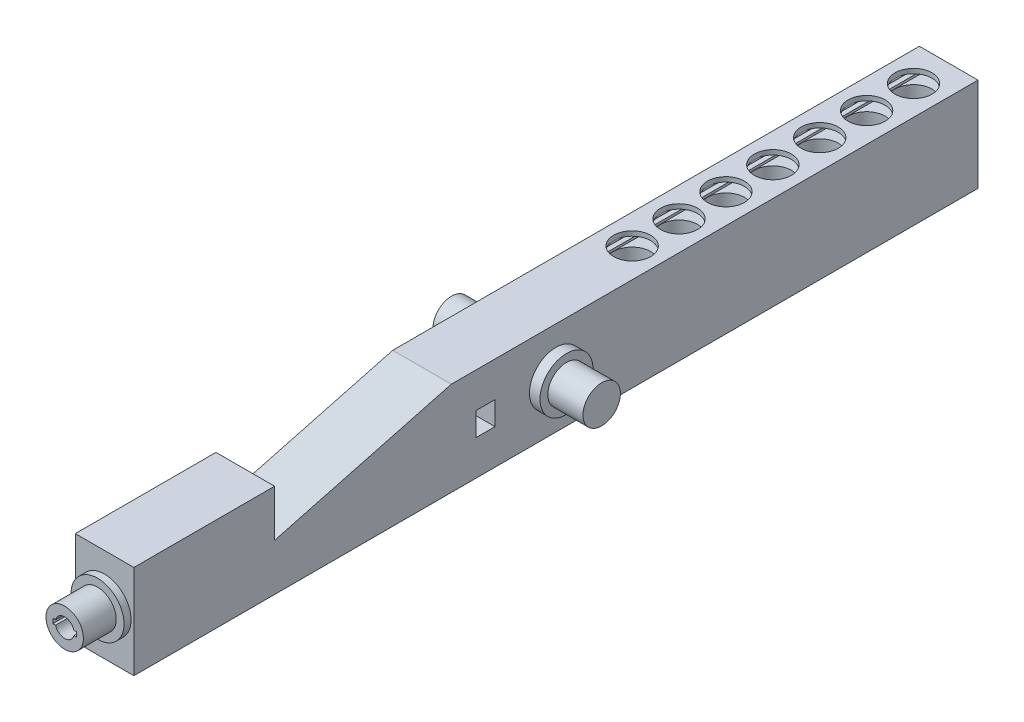
SolidWorks part; units mm, degrees
material "6061 Alloy"
ref_plane "Front Plane" through (0, 0, 0) normal (0, 0, 1) x (1, 0, 0)
ref_plane "Top Plane" through (0, 0, 0) normal (0, 1, 0) x (1, 0, 0)
ref_plane "Right Plane" through (0, 0, 0) normal (1, 0, 0) x (0, 0, -1)
sketch "Sketch1" plane through (0, 0, 0) normal (0, 1, 0) x (1, 0, 0)
  line L1 (-6.25, 90) -> (6.25, 90)
  line L2 (-6.25, 90) -> (-6.25, -90)
  line L3 (-6.25, -90) -> (6.25, -90)
  line L4 (6.25, 90) -> (6.25, -90)
  line L5 (-6.25, 90) -> (6.25, -90) construction
  line L6 (-6.25, -90) -> (6.25, 90) construction
  point P0 (0, 0)
  dimension "D1" = 12.5
  dimension "D2" = 180
extrude "Boss-Extrude1" add sketch "Sketch1" along normal blind 20
sketch "Sketch2" plane through (0, 0, 90) normal (0, 0, 1) x (1, 0, 0)
  line L0 (0, 0) -> (0, 10) construction
  line L1 (-6.25, 0) -> (6.25, 0) construction
  circle A0 centre (0, 10) radius 5.65
  dimension "D2" = 11.3
  dimension "D1" = 10
extrude "Boss-Extrude2" add sketch "Sketch2" along normal blind 1.5
sketch "Sketch3" plane through (0, 0, 91.5) normal (0, 0, 1) x (1, 0, 0)
  line L0 (0, 0) -> (0, 10) construction
  circle A0 centre (0, 10) radius 3.99
  dimension "D1" = 7.98
extrude "Boss-Extrude3" add sketch "Sketch3" along normal blind 7
sketch "Sketch4" plane through (-6.25, 0, 0) normal (-1, 0, 0) x (0, 0, 1)
  line L0 (0, 0) -> (0, 10) construction
  circle A0 centre (0, 10) radius 5.65
  dimension "D2" = 11.3
  dimension "D1" = 10
extrude "Boss-Extrude4" add sketch "Sketch4" along normal blind 2.25
sketch "Sketch5" plane through (-8.5, 0, 0) normal (-1, 0, 0) x (0, 0, 1)
  line L0 (0, 0) -> (0, 10) construction
  line L1 (-90, 0) -> (90, 0) construction
  circle A0 centre (0, 10) radius 3.99
  dimension "D1" = 7.98
extrude "Boss-Extrude5" add sketch "Sketch5" along normal blind 7.5
sketch "Sketch6" plane through (6.25, 0, 0) normal (1, 0, 0) x (0, 0, -1)
  line L0 (0, 0) -> (0, 10) construction
  circle A0 centre (0, 10) radius 5.65
  dimension "D2" = 11.3
  dimension "D1" = 10
extrude "Boss-Extrude6" add sketch "Sketch6" along normal blind 2.25
sketch "Sketch7" plane through (8.5, 0, 0) normal (1, 0, 0) x (0, 0, -1)
  line L0 (0, 0) -> (0, 10) construction
  circle A0 centre (0, 10) radius 3.99
  dimension "D1" = 7.98
extrude "Boss-Extrude7" add sketch "Sketch7" along normal blind 7.5
sketch "Sketch8" plane through (0, 20, 0) normal (0, 1, 0) x (1, 0, 0)
  line L0 (0, 0) -> (0, 90) construction
  line L1 (6.25, 90) -> (-6.25, 90) construction
  circle A0 centre (0, 82.5) radius 3.95
  circle A1 centre (0, 72.5) radius 3.95
  circle A2 centre (0, 62.5) radius 3.95
  circle A3 centre (0, 52.5) radius 3.95
  circle A4 centre (0, 42.5) radius 3.95
  circle A5 centre (0, 32.5) radius 3.95
  circle A6 centre (0, 22.5) radius 3.95
  dimension "D1" = 7.9
  dimension "D2" = 7.9
  dimension "D3" = 7.9
  dimension "D4" = 7.9
  dimension "D5" = 7.9
  dimension "D6" = 7.9
  dimension "D13" = 7.9
  dimension "D7" = 7.5
  dimension "D8" = 10
  dimension "D9" = 10
  dimension "D10" = 10
  dimension "D11" = 10
  dimension "D12" = 10
  dimension "D14" = 10
extrude "Cut-Extrude1" cut sketch "Sketch8" against normal blind 19
sketch "Sketch9" plane through (0, 0, -90) normal (0, 0, -1) x (-1, 0, 0)
  line L0 (0, 0) -> (0, 18) construction
  line L2 (-4, 19) -> (4, 19)
  line L3 (-4, 19) -> (-4, 17)
  line L4 (-4, 17) -> (4, 17)
  line L5 (4, 19) -> (4, 17)
  line L6 (-4, 19) -> (4, 17) construction
  line L7 (-4, 17) -> (4, 19) construction
  dimension "D1" = 18
  dimension "D2" = 8
  dimension "D3" = 2
extrude "Cut-Extrude2" cut sketch "Sketch9" against normal blind 72.5
sketch "Sketch10" plane through (0, 0, -90) normal (0, 0, -1) x (-1, 0, 0)
  line L0 (0, 0) -> (0, 18) construction
  line L1 (-6.25, 0) -> (6.25, 0) construction
  line L3 (-5.75, 18.5) -> (5.75, 18.5)
  line L4 (-5.75, 18.5) -> (-5.75, 17.5)
  line L5 (-5.75, 17.5) -> (5.75, 17.5)
  line L6 (5.75, 18.5) -> (5.75, 17.5)
  line L7 (-5.75, 18.5) -> (5.75, 17.5) construction
  line L8 (-5.75, 17.5) -> (5.75, 18.5) construction
  dimension "D1" = 18
  dimension "D2" = 11.5
  dimension "D3" = 1
extrude "Cut-Extrude3" cut sketch "Sketch10" against normal blind 72.5
sketch "Sketch12" plane through (0, 0, 98.5) normal (0, 0, 1) x (1, 0, 0)
  line L0 (1.9365, 10.5) -> (2.5, 10.5)
  line L1 (-2.5, 9.5) -> (-1.9365, 9.5)
  line L2 (-2.5, 9.5) -> (-2.5, 10.5)
  line L3 (-2.5, 10.5) -> (-1.9365, 10.5)
  line L4 (2.5, 9.5) -> (2.5, 10.5)
  line L5 (-2.5, 9.5) -> (2.5, 10.5) construction
  line L6 (-2.5, 10.5) -> (2.5, 9.5) construction
  line L7 (1.9365, 9.5) -> (2.5, 9.5)
  arc A0 (-1.9365, 9.5) -> (1.9365, 9.5) centre (0, 10) ccw
  arc A1 (1.9365, 10.5) -> (-1.9365, 10.5) centre (0, 10) ccw
  dimension "D1" = 4
  dimension "D2" = 5
  dimension "D3" = 1
extrude "Cut-Extrude5" cut sketch "Sketch12" against normal blind 20
sketch "Sketch14" plane through (6.25, 0, 0) normal (1, 0, 0) x (0, 0, -1)
  line L0 (0, 10) -> (-15, 10) construction
  line L2 (-17, 12.5) -> (-13, 12.5)
  line L3 (-17, 12.5) -> (-17, 7.5)
  line L4 (-17, 7.5) -> (-13, 7.5)
  line L5 (-13, 12.5) -> (-13, 7.5)
  line L6 (-17, 12.5) -> (-13, 7.5) construction
  line L7 (-17, 7.5) -> (-13, 12.5) construction
  dimension "D1" = 15
  dimension "D2" = 5
  dimension "D3" = 4
extrude "Cut-Extrude6" cut sketch "Sketch14" against normal up to surface (12.5 mm away) up to face at (-6.25, 10, -5.65)
sketch "Sketch11" plane through (0, 20, 0) normal (0, 1, 0) x (1, 0, 0)
  line L0 (0, 0) -> (0, -35) construction
  line L1 (6.25, -90) -> (6.25, 90) construction
  line L2 (-6.25, -45.75) -> (6.25, -45.75)
  line L3 (-6.25, -45.75) -> (-6.25, -24.25)
  line L4 (-6.25, -24.25) -> (6.25, -24.25)
  line L5 (6.25, -45.75) -> (6.25, -24.25)
  line L6 (-6.25, -45.75) -> (6.25, -24.25) construction
  line L7 (-6.25, -24.25) -> (6.25, -45.75) construction
  dimension "D1" = 35
  dimension "D2" = 21.5
extrude "Cut-Extrude4" [suppressed] cut sketch "Sketch11" against normal blind 7
sketch "Sketch15" plane through (6.25, 0, 0) normal (1, 0, 0) x (0, 0, -1)
  line L0 (0, 10) -> (-60, 10) construction
  line L1 (-60, 10) -> (-60, 20)
  line L2 (-90, 20) -> (90, 20) construction
  line L3 (-60, 10) -> (-22.3038, 20)
  line L4 (-22.3038, 20) -> (-60, 20)
  dimension "D1" = 60
  dimension "D2" = 39
extrude "Cut-Extrude7" cut sketch "Sketch15" against normal up to next
